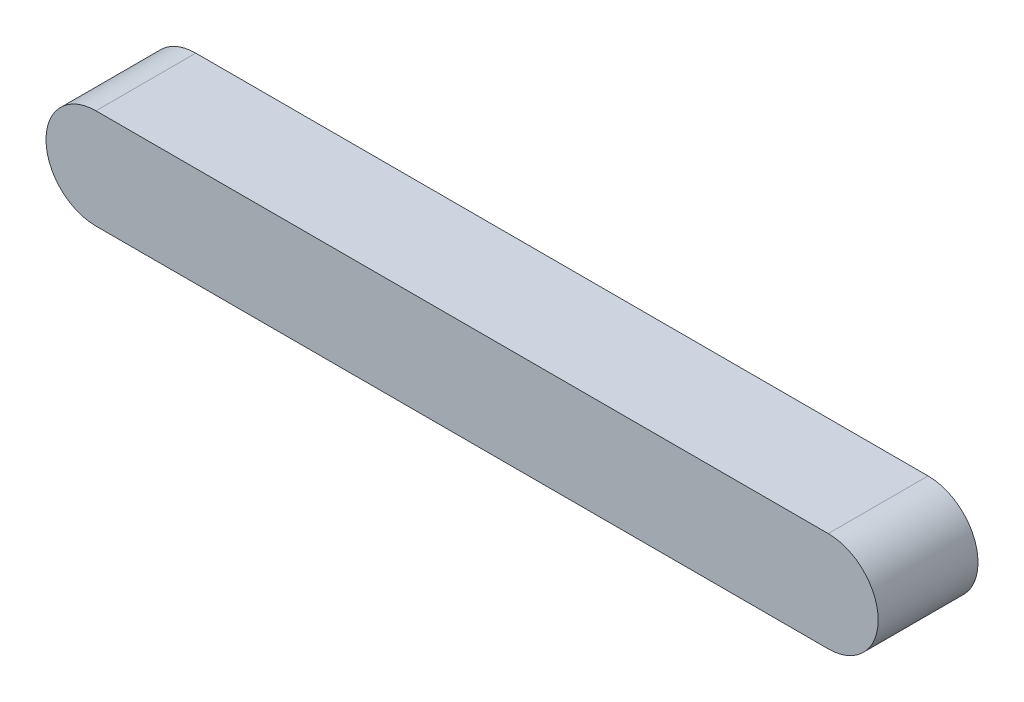
SolidWorks part; units mm, degrees
material "Plain Carbon Steel"
ref_plane "Front Plane" through (0, 0, 0) normal (0, 0, 1) x (1, 0, 0)
ref_plane "Top Plane" through (0, 0, 0) normal (0, 1, 0) x (1, 0, 0)
ref_plane "Right Plane" through (0, 0, 0) normal (1, 0, 0) x (0, 0, -1)
sketch "Sketch1" plane through (0, 0, 0) normal (0, 0, 1) x (1, 0, 0)
  line L0 (-44, 0) -> (44, 0) construction
  line L1 (-44, 6) -> (44, 6)
  line L2 (-44, -6) -> (44, -6)
  line L3 (-40.188, 0) -> (46.724, 0) construction
  line L4 (-50, 0) -> (-50, 16.5501) construction
  line L5 (50, 0) -> (50, 15.8403) construction
  arc A0 (-44, 6) -> (-44, -6) centre (-44, 0) ccw
  arc A1 (44, -6) -> (44, 6) centre (44, 0) ccw
  point P2 (0, 0)
  dimension "D2" = 6
  dimension "D1" = 100
extrude "Boss-Extrude1" add sketch "Sketch1" along normal blind 12
